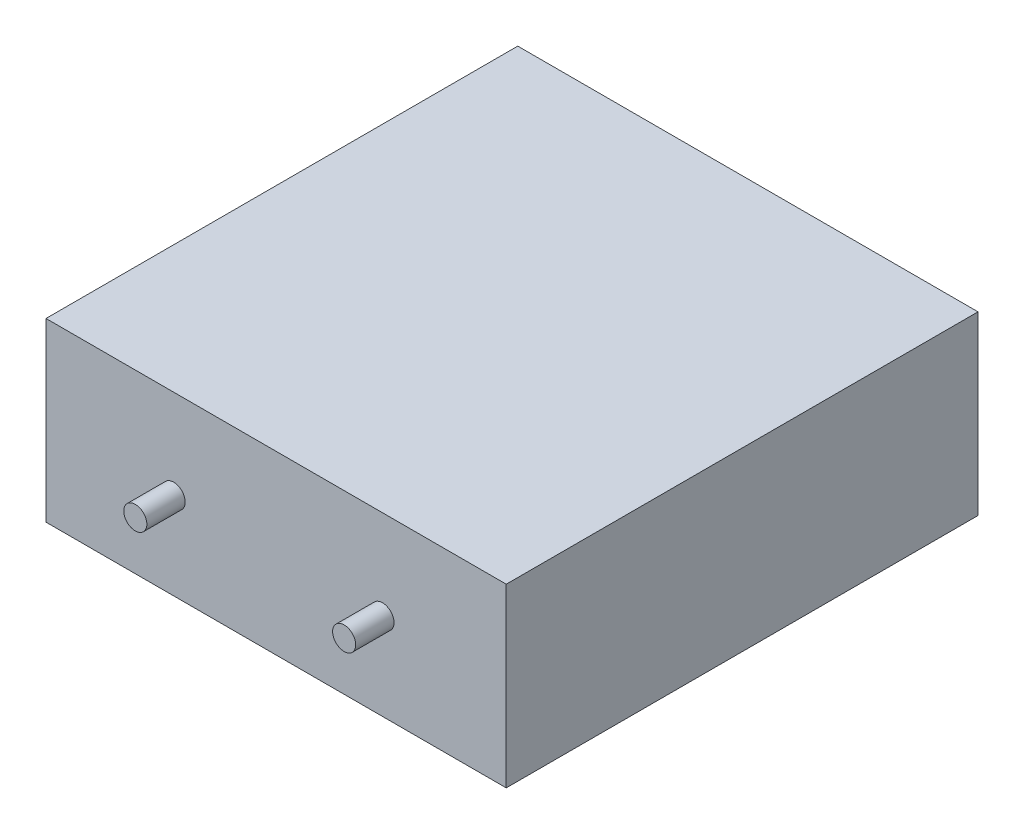
SolidWorks part; units mm, degrees
ref_plane "Ebene vorne" through (0, 0, 0) normal (0, 0, 1) x (1, 0, 0)
ref_plane "Ebene oben" through (0, 0, 0) normal (0, 1, 0) x (1, 0, 0)
ref_plane "Ebene rechts" through (0, 0, 0) normal (1, 0, 0) x (0, 0, -1)
sketch "Skizze1" plane through (0, 0, 0) normal (0, 1, 0) x (1, 0, 0)
  line L1 (60, -61.5) -> (-60, -61.5)
  line L2 (60, -61.5) -> (60, 61.5)
  line L3 (60, 61.5) -> (-60, 61.5)
  line L4 (-60, -61.5) -> (-60, 61.5)
  line L5 (60, -61.5) -> (-60, 61.5) construction
  line L6 (60, 61.5) -> (-60, -61.5) construction
  point P0 (0, 0)
  dimension "D1" = 123
  dimension "D2" = 120
extrude "Aufsatz-Linear austragen1" add sketch "Skizze1" along normal blind 46
sketch "Skizze2" plane through (0, 0, 61.5) normal (0, 0, 1) x (1, 0, 0)
  circle A0 centre (-26.717, 22.6698) radius 3.0073
  circle A1 centre (27.7377, 22.6698) radius 3.0073
extrude "Aufsatz-Linear austragen2" add sketch "Skizze2" along normal blind 10
